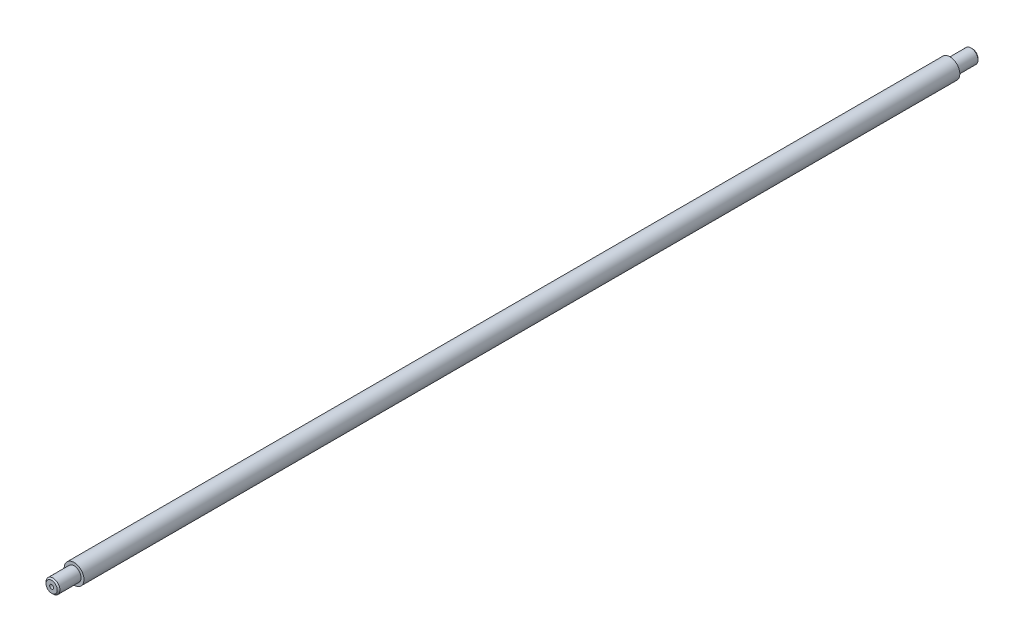
SolidWorks part; units mm, degrees
material "Balsa"
ref_plane "Front Plane" through (0, 0, 0) normal (0, 0, 1) x (1, 0, 0)
ref_plane "Top Plane" through (0, 0, 0) normal (0, 1, 0) x (1, 0, 0)
ref_plane "Right Plane" through (0, 0, 0) normal (1, 0, 0) x (0, 0, -1)
sketch "Sketch2" plane through (0, 0, 0) normal (0, 0, 1) x (1, 0, 0)
  circle A0 centre (0, 0) radius 5.588
  dimension "D1" = 11.176
extrude "Boss-Extrude1" add sketch "Sketch2" along normal mid plane 495.3
sketch "Sketch3" plane through (0, 0, 247.65) normal (0, 0, 1) x (1, 0, 0)
  circle A0 centre (0, 0) radius 3.937
  circle A1 centre (0, 0) radius 5.588
  circle A2 centre (0, 0) radius 5.588
  dimension "D2" = 7.874
  dimension "D1" = 0
extrude "Boss-Extrude2" add sketch "Sketch3" along normal blind 12.7 contours A0
sketch "Sketch4" plane through (0, 0, -247.65) normal (0, 0, -1) x (-1, 0, 0)
  circle A0 centre (0, 0) radius 3.937
  circle A1 centre (0, 0) radius 5.588
  circle A2 centre (0, 0) radius 5.588
  dimension "D2" = 7.874
  dimension "D1" = 0
extrude "Boss-Extrude3" add sketch "Sketch4" along normal blind 12.7 contours A0
sketch "Sketch5" plane through (0, 0, 260.35) normal (0, 0, 1) x (1, 0, 0)
  circle A0 centre (0, 0) radius 1.143
  circle A1 centre (0, 0) radius 3.937
  circle A2 centre (0, 0) radius 3.937
  dimension "D2" = 2.286
  dimension "D1" = 0
extrude "Cut-Extrude1" cut sketch "Sketch5" against normal blind 25.4 contours A0
sketch "Sketch6" plane through (0, 0, -260.35) normal (0, 0, -1) x (-1, 0, 0)
  circle A0 centre (0, 0) radius 1.143
  circle A1 centre (0, 0) radius 3.937
  circle A2 centre (0, 0) radius 3.937
  dimension "D2" = 2.286
  dimension "D1" = 0
extrude "Cut-Extrude2" cut sketch "Sketch6" against normal blind 25.4 contours A0
chamfer "Chamfer2" distance 0.762 angle 45 2 edges at (-3.937, 0, -260.35) (3.937, 0, 260.35)
